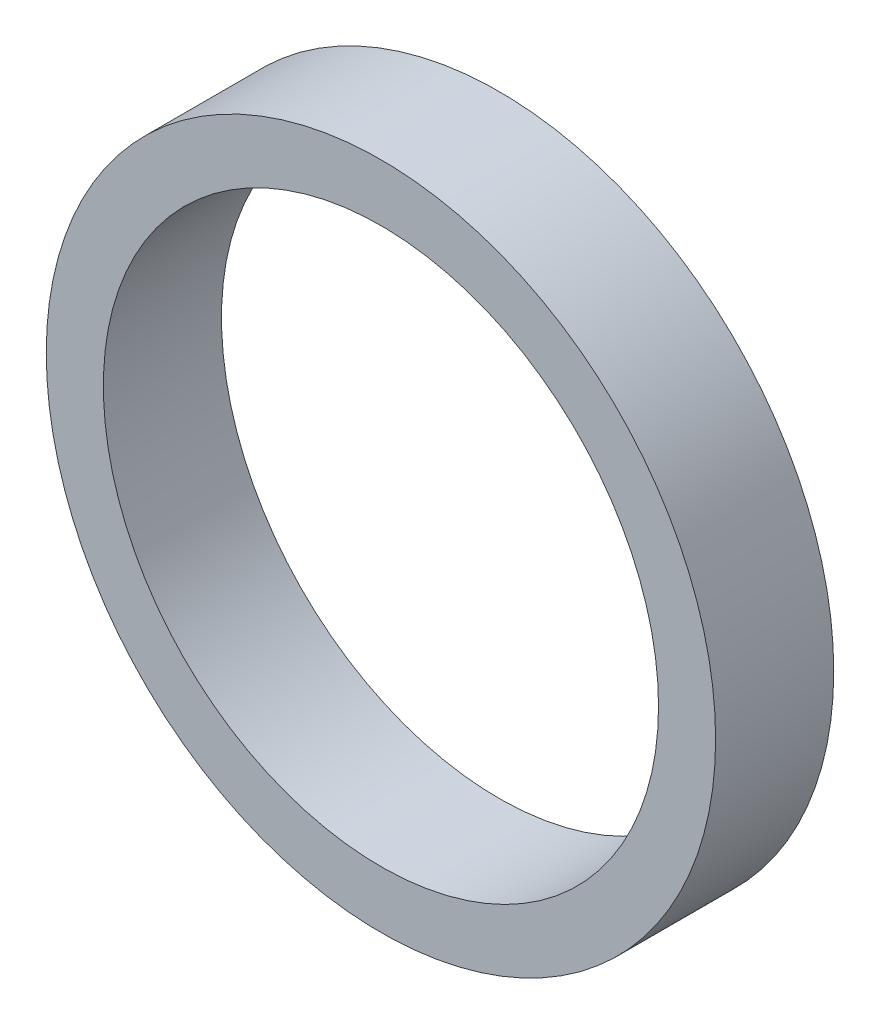
SolidWorks part; units mm, degrees
material "Rubber"
ref_plane "Front Plane" through (0, 0, 0) normal (0, 0, 1) x (1, 0, 0)
ref_plane "Top Plane" through (0, 0, 0) normal (0, 1, 0) x (1, 0, 0)
ref_plane "Right Plane" through (0, 0, 0) normal (1, 0, 0) x (0, 0, -1)
sketch "Sketch1" plane through (0, 0, 0) normal (0, 0, 1) x (1, 0, 0)
  circle A0 centre (0, 0) radius 21.59
  dimension "D1" = 43.18
extrude "Boss-Extrude1" add sketch "Sketch1" along normal blind 7.62 contours A0
sketch "Sketch2" plane through (0, 0, 7.62) normal (0, 0, 1) x (1, 0, 0)
  circle A0 centre (0, 0) radius 17.907
extrude "Cut-Extrude1" cut sketch "Sketch2" against normal blind 7.62
